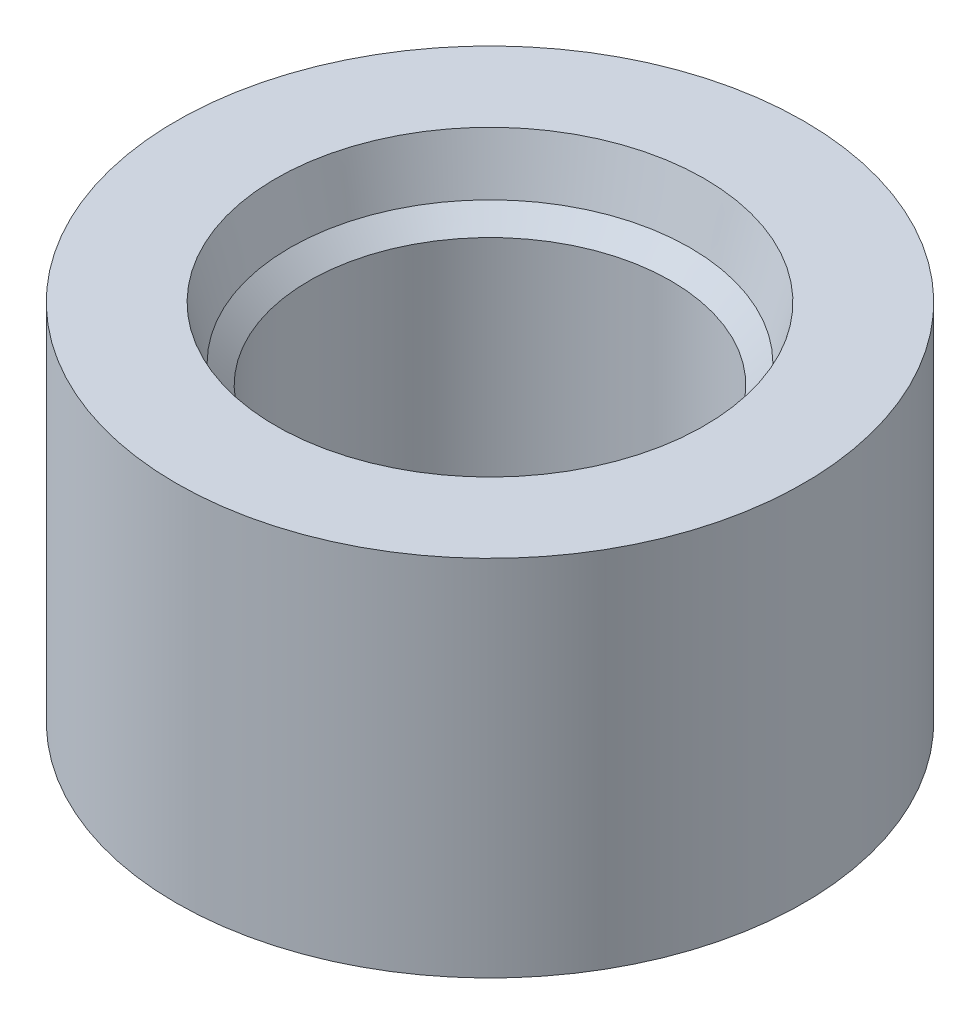
SolidWorks part; units mm, degrees
material "AISI 316 Annealed Stainless Steel Bar (SS)"
ref_plane "Front Plane" through (0, 0, 0) normal (0, 0, 1) x (1, 0, 0)
ref_plane "Top Plane" through (0, 0, 0) normal (0, 1, 0) x (1, 0, 0)
ref_plane "Right Plane" through (0, 0, 0) normal (1, 0, 0) x (0, 0, -1)
sketch "Sketch1" plane through (0, 0, 0) normal (0, 0, 1) x (1, 0, 0)
  line L0 (0, 0) -> (0, 35.7987) construction
  line L1 (8.6995, 0) -> (8.6995, 14.0156)
  line L2 (8.6995, 14.0156) -> (9.6191, 14.9352)
  line L3 (9.6191, 14.9352) -> (10.2997, 17.4752)
  line L4 (10.2997, 17.4752) -> (15.0876, 17.4752)
  line L5 (15.0876, 17.4752) -> (15.0876, 0)
  line L6 (15.0876, 0) -> (8.6995, 0)
  line L7 (10.2997, 17.4752) -> (10.2997, 13.3666) construction
  dimension "D1" = 17.4752
  dimension "D2" = 2.54
  dimension "D3" = 15
  dimension "D4" = 45
  dimension "D5" = 17.399
  dimension "D7" = 30.1752
revolve "Revolve1" add sketch "Sketch1" angle 360 about L0
